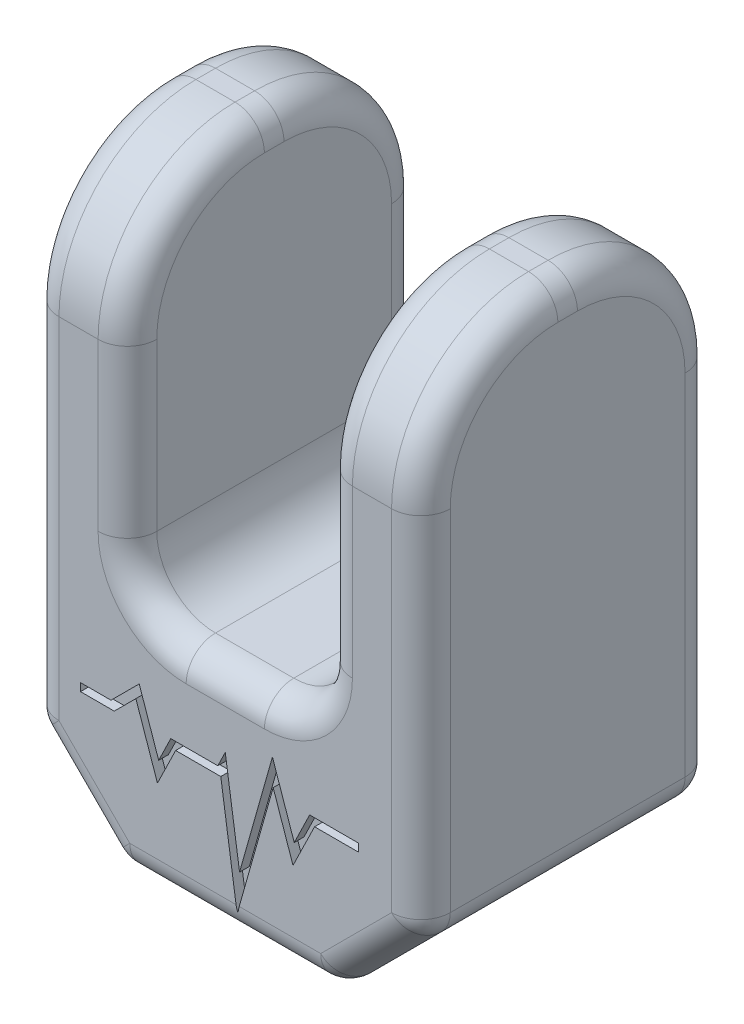
SolidWorks part; units mm, degrees
material "ABS"
ref_plane "Plan de face" through (0, 0, 0) normal (0, 0, 1) x (1, 0, 0)
ref_plane "Plan de dessus" through (0, 0, 0) normal (0, 1, 0) x (1, 0, 0)
ref_plane "Plan de droite" through (0, 0, 0) normal (1, 0, 0) x (0, 0, -1)
sketch "Esquisse1" plane through (0, 0, 0) normal (0, 0, 1) x (1, 0, 0)
  line L1 (-10, 15) -> (10, 15)
  line L2 (-10, 15) -> (-10, -15)
  line L3 (-10, -15) -> (10, -15)
  line L4 (10, 15) -> (10, -15)
  line L5 (-10, 15) -> (10, -15) construction
  line L6 (-10, -15) -> (10, 15) construction
  point P0 (0, 0)
  dimension "D1" = 30
  dimension "D2" = 20
extrude "Boss.-Extru.1" add sketch "Esquisse1" along normal blind 15
fillet "Congé1" radius 7 2 edges at (0, 15, 0) (0, 15, 15)
ref_plane "Plan1" through (0, 15, 0) normal (0, 1, 0) x (1, 0, 0)
sketch "Esquisse2" plane through (0, 15, 0) normal (0, 1, 0) x (1, 0, 0)
  line L0 (0, 0) -> (0, -23.165) construction
  line L1 (-5, 0) -> (-5, -15)
  line L2 (-10, 0) -> (10, 0) construction
  line L3 (10, -15) -> (-10, -15) construction
  line L4 (-5, -15) -> (5, -15)
  line L5 (5, -15) -> (5, 0)
  line L6 (5, 0) -> (-5, 0)
  dimension "D1" = 10
extrude "Enlèv. mat.-Extru.1" cut sketch "Esquisse2" against normal blind 18.5
fillet "Congé2" radius 3 2 edges at (-5, -3.5, 7.5) (5, -3.5, 7.5)
fillet "Congé3" radius 1.5 16 edges at (4.1213, -2.6213, 15) (0, -3.5, 15) (-4.1213, -2.6213, 15) (-5, 3.75, 15) (-5, 12.9497, 12.9497) (-5, 12.9497, 2.0503) (-5, 3.75, 0) (-4.1213, -2.6213, 0) (0, -3.5, 0) (4.1213, -2.6213, 0) (5, 3.75, 0) (5, 12.9497, 2.0503) (5, 12.9497, 12.9497) (5, 3.75, 15) (-5, 15, 7.5) (5, 15, 7.5)
chamfer "Chanfrein1" distance 4.5 angle 45 2 edges at (10, -15, 7.5) (-10, -15, 7.5)
fillet "Congé4" radius 1.5 20 edges at (10, -1.25, 0) (10, 12.9497, 2.0503) (10, 12.9497, 12.9497) (-10, -1.25, 0) (-10, 12.9497, 2.0503) (-10, 12.9497, 12.9497) (10, -10.5, 7.5) (-10, -10.5, 7.5) (-5.5, -15, 7.5) (5.5, -15, 7.5) (7.75, -12.75, 0) (0, -15, 0) (-7.75, -12.75, 0) (-7.75, -12.75, 15) (0, -15, 15) (7.75, -12.75, 15) (10, -1.25, 15) (-10, -1.25, 15) (10, 15, 7.5) (-10, 15, 7.5)
sketch "Esquisse3" plane through (0, 0, 15) normal (0, 0, 1) x (1, 0, 0)
  line L16 (6.7997, -7.6454) -> (4.3133, -7.6454)
  line L17 (4.3133, -7.6454) -> (3.5254, -9.2635)
  line L18 (3.5254, -9.2635) -> (2.4114, -6.0348)
  line L19 (2.4114, -6.0348) -> (0.7302, -11.9714)
  line L20 (0.7302, -11.9714) -> (0, -7.0354)
  line L21 (0, -7.0354) -> (-0.3809, -7.8177)
  line L22 (-0.3809, -7.8177) -> (-2.7854, -7.8177)
  line L23 (-2.7854, -7.8177) -> (-3.4036, -9.0874)
  line L24 (-3.4036, -9.0874) -> (-4.3988, -6.2034)
  line L25 (-4.3988, -6.2034) -> (-5.8408, -7.6454)
  line L26 (-5.8408, -7.6454) -> (-7.3992, -7.6454)
  line L27 (6.7997, -8.0454) -> (4.5635, -8.0454)
  line L28 (4.5635, -8.0454) -> (3.4623, -10.3068)
  line L29 (3.4623, -10.3068) -> (2.449, -7.3701)
  line L30 (2.449, -7.3701) -> (0.6072, -13.8736)
  line L31 (0.6072, -13.8736) -> (-0.2295, -8.2177)
  line L32 (-0.2295, -8.2177) -> (-0.2295, -8.2177)
  line L33 (-0.2295, -8.2177) -> (-2.5352, -8.2177)
  line L34 (-2.5352, -8.2177) -> (-3.4668, -10.1308)
  line L35 (-3.4668, -10.1308) -> (-4.5682, -6.9386)
  line L36 (-4.5682, -6.9386) -> (-5.6751, -8.0454)
  line L37 (-5.6751, -8.0454) -> (-7.3992, -8.0454)
  line L38 (-7.3992, -8.0454) -> (-7.3992, -7.6454)
  line L39 (6.7997, -8.0454) -> (6.7997, -7.6454)
  dimension "D1" = 0.4
extrude "Enlèv. mat.-Extru.2" cut sketch "Esquisse3" against normal blind 0.5
sketch "Esquisse4" plane through (-10, 0, 0) normal (-1, 0, 0) x (0, 0, 1)
  line L0 (8, 13.5) -> (8, 10.8526) construction
  line L1 (9.2413, 9.2829) -> (8, 10.8526)
  line L2 (8, 10.8526) -> (6.7587, 9.2829)
  line L3 (8, 8.0417) -> (8, -14.568) construction
  arc A0 (6.7587, 9.2829) -> (8, 8.0417) centre (7.4519, 8.7348) ccw
  arc A1 (9.2413, 9.2829) -> (8, 8.0417) centre (8.5481, 8.7348) cw
extrude "Enlèv. mat.-Extru.3" cut sketch "Esquisse4" against normal blind 0.5
